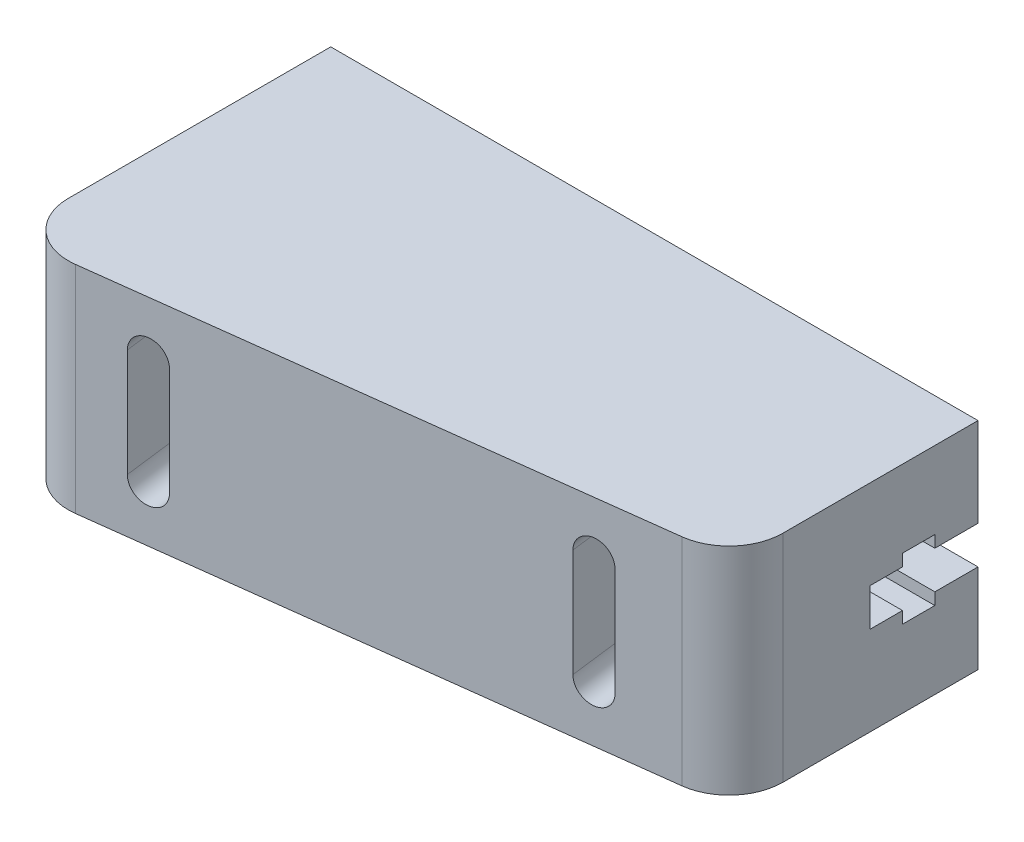
SolidWorks part; units mm, degrees
ref_plane "Front Plane" through (0, 0, 0) normal (0, 0, 1) x (1, 0, 0)
ref_plane "Top Plane" through (0, 0, 0) normal (0, 1, 0) x (1, 0, 0)
ref_plane "Right Plane" through (0, 0, 0) normal (1, 0, 0) x (0, 0, -1)
sketch "Sketch1" plane through (0, 0, 0) normal (0, 0, 1) x (1, 0, 0)
  line L1 (-30, 10) -> (30, 10)
  line L2 (-30, 10) -> (-30, -10)
  line L3 (-30, -10) -> (30, -10)
  line L4 (30, 10) -> (30, -10)
  line L5 (-30, 10) -> (30, -10) construction
  line L6 (-30, -10) -> (30, 10) construction
  point P0 (0, 0)
  dimension "D1" = 60
  dimension "D2" = 20
extrude "Boss-Extrude1" add sketch "Sketch1" along normal blind 30
sketch "Sketch2" plane through (0, 10, 0) normal (0, 1, 0) x (1, 0, 0)
  line L0 (-30, -30) -> (30, -30)
  line L1 (30, -30) -> (30, -22.5)
  line L2 (30, -30) -> (30, 0) construction
  line L3 (30, -22.5) -> (-30, -30)
  dimension "D1" = 7.5
extrude "Cut-Extrude1" cut sketch "Sketch2" against normal through all
sketch "Sketch3" plane through (0, 10, 0) normal (0, 1, 0) x (1, 0, 0)
  line L6 (-25, 0) -> (25, 0)
  line L9 (25, 0) -> (25, -18.0861)
  line L10 (25, -18.0861) -> (-25, -24.3361)
  line L11 (-25, -24.3361) -> (-25, 0)
  line L12 (25, 0) -> (25, -18.0861)
  line L13 (25, -18.0861) -> (-25, -24.3361)
  line L14 (-25, -24.3361) -> (-25, 0)
  dimension "D1" = 5
extrude "Cut-Extrude2" cut sketch "Sketch3" against normal through all from offset 4 offset against normal yes
sketch "Sketch4" plane through (-30, 0, 0) normal (-1, 0, 0) x (0, 0, 1)
  line L0 (0, 0) -> (30, 0) construction
  line L1 (30, 10) -> (30, -10) construction
  line L2 (0, 1.75) -> (4, 1.75)
  line L3 (0, 10) -> (0, -10) construction
  line L4 (4, 1.75) -> (4, 2.85)
  line L5 (4, 2.85) -> (7, 2.85)
  line L6 (7, 2.85) -> (7, 1.75)
  line L7 (7, 1.75) -> (10, 1.75)
  line L8 (10, 1.75) -> (10, -1.75)
  line L9 (7, -1.75) -> (10, -1.75)
  line L10 (7, -2.85) -> (7, -1.75)
  line L11 (4, -2.85) -> (7, -2.85)
  line L12 (4, -1.75) -> (4, -2.85)
  line L13 (0, -1.75) -> (4, -1.75)
  line L14 (0, 1.75) -> (0, -1.75)
  point P15 (10, 0)
  dimension "D1" = 3
  dimension "D2" = 5.7
  dimension "D3" = 3.5
  dimension "D4" = 10
  dimension "D5" = 4
extrude "Cut-Extrude3" cut sketch "Sketch4" against normal through all
sketch "Sketch5" plane through (3.2308, 0, 25.8462) normal (0.124, 0, 0.9923) x (0.9923, 0, -0.124)
  line L0 (-21.7559, 5) -> (-21.7559, -5) construction
  line L1 (-20.0059, 5) -> (-20.0059, -5)
  line L2 (-23.5059, 5) -> (-23.5059, -5)
  line L3 (15.2441, 5) -> (15.2441, -5) construction
  line L4 (16.9941, 5) -> (16.9941, -5)
  line L5 (13.4941, 5) -> (13.4941, -5)
  line L6 (-21.7559, 0) -> (15.2441, 0) construction
  line L7 (26.9776, 10) -> (-33.4894, 10) construction
  line L8 (-33.4894, 10) -> (-33.4894, -10) construction
  arc A0 (-20.0059, 5) -> (-23.5059, 5) centre (-21.7559, 5) ccw
  arc A1 (-23.5059, -5) -> (-20.0059, -5) centre (-21.7559, -5) ccw
  arc A2 (16.9941, 5) -> (13.4941, 5) centre (15.2441, 5) ccw
  arc A3 (13.4941, -5) -> (16.9941, -5) centre (15.2441, -5) ccw
  point P2 (-21.7559, 0)
  point P7 (15.2441, 0)
  point P16 (-3.2559, 0)
  point P19 (-3.2559, 10)
  point P20 (16.9941, -5.0856)
  point P23 (-33.4894, 0)
  dimension "D1" = 1.75
  dimension "D2" = 37
  dimension "D3" = 10
extrude "Cut-Extrude4" cut sketch "Sketch5" against normal up to surface (5 mm away) up to face at (0, -2, 21.2111)
fillet "Fillet1" radius 5 2 edges at (30, 0, 22.5) (-30, 0, 30)
